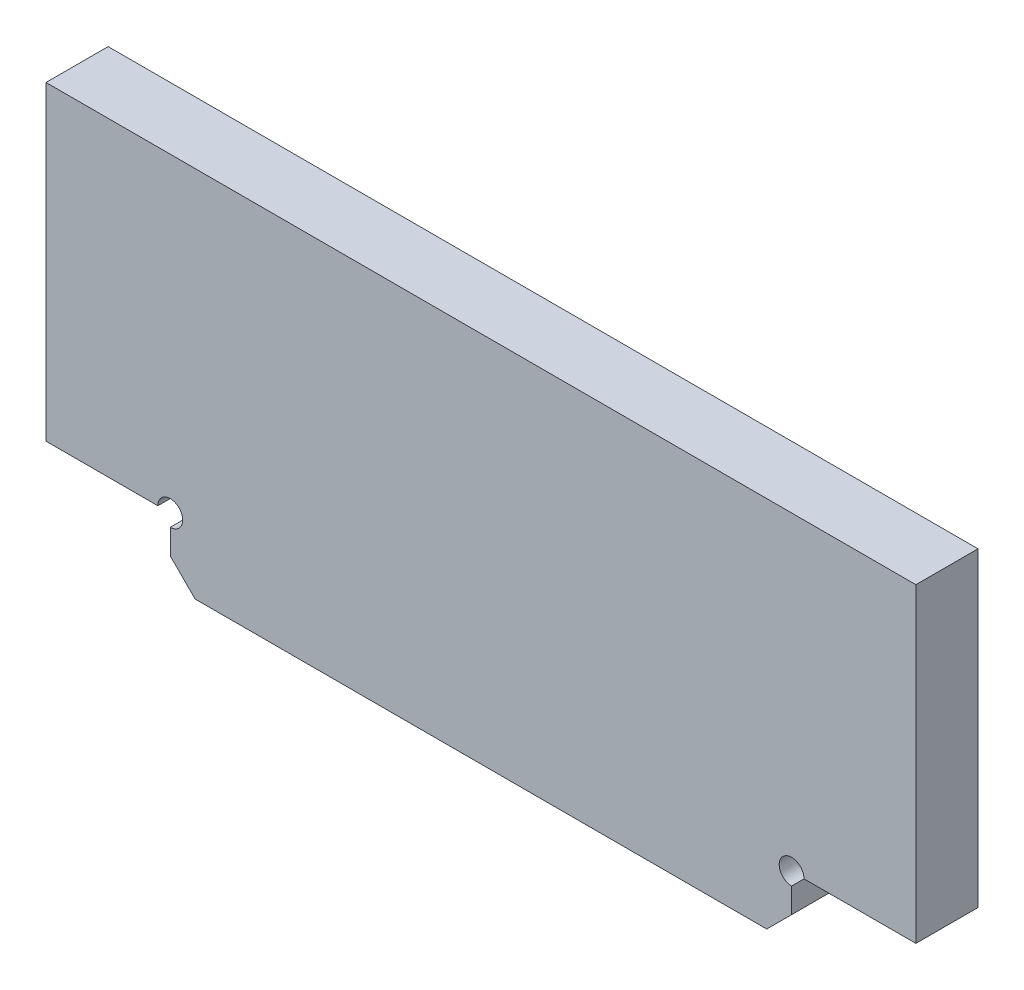
SolidWorks part; units mm, degrees
ref_plane "前基準面" through (0, 0, 0) normal (0, 0, 1) x (1, 0, 0)
ref_plane "上基準面" through (0, 0, 0) normal (0, 1, 0) x (1, 0, 0)
ref_plane "右基準面" through (0, 0, 0) normal (1, 0, 0) x (0, 0, -1)
sketch "草圖1" plane through (0, 0, 0) normal (0, 0, 1) x (1, 0, 0)
  line L0 (-25, 2) -> (-23, 0)
  line L3 (-23, 0) -> (23, 0)
  line L5 (23, 0) -> (25, 2)
  line L6 (-25, 2) -> (-25, 4)
  line L9 (35, 30) -> (-35, 30)
  line L10 (-35, 5) -> (-35, 30)
  line L14 (35, 5) -> (35, 30)
  line L15 (-26, 5) -> (-35, 5)
  line L16 (25, 2) -> (25, 4)
  line L17 (26, 5) -> (35, 5)
  arc A0 (-25, 4) -> (-26, 5) centre (-25, 5) ccw
  arc A1 (26, 5) -> (25, 4) centre (25, 5) ccw
  point P1 (25, 0)
  point P2 (-25, 0)
  point P8 (0, 0)
  point P20 (0, 30)
  dimension "D8" = 1
  dimension "D1" = 50
  dimension "D2" = 70
  dimension "D3" = 25
  dimension "D7" = 3
extrude "填料-伸長1" add sketch "草圖1" along normal mid plane 5 contours L9 L10 L15 A0 L6 L0 L3 L5 L16 A1 L17 L14
